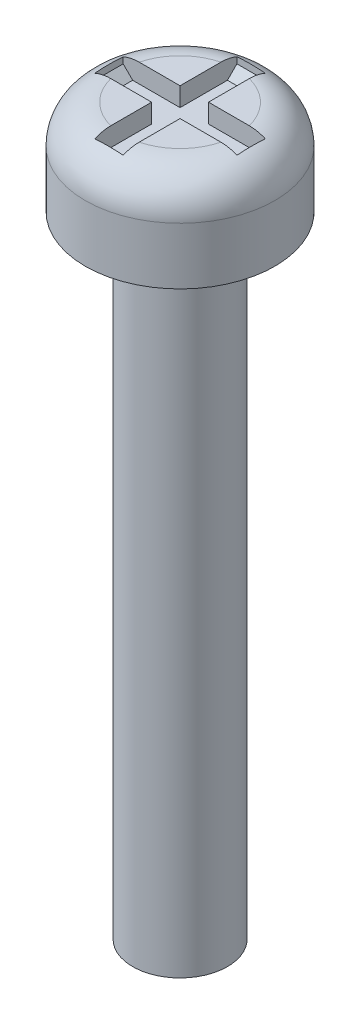
SolidWorks part; units mm, degrees
ref_plane "Front Plane" through (0, 0, 0) normal (0, 0, 1) x (1, 0, 0)
ref_plane "Top Plane" through (0, 0, 0) normal (0, 1, 0) x (1, 0, 0)
ref_plane "Right Plane" through (0, 0, 0) normal (1, 0, 0) x (0, 0, -1)
sketch "Sketch1" plane through (0, 0, 0) normal (0, 1, 0) x (1, 0, 0)
  circle A0 centre (0, 0) radius 2
  dimension "D1" = 4
extrude "Boss-Extrude1" add sketch "Sketch1" along normal blind 2
fillet "Fillet1" radius 0.8 1 edges at (0, 2, 2)
sketch "Sketch2" plane through (0, 2, 0) normal (0, 1, 0) x (1, 0, 0)
  line L1 (-1.5, 0.3) -> (1.5, 0.3)
  line L2 (-1.5, 0.3) -> (-1.5, -0.3)
  line L3 (-1.5, -0.3) -> (1.5, -0.3)
  line L4 (1.5, 0.3) -> (1.5, -0.3)
  line L5 (-1.5, 0.3) -> (1.5, -0.3) construction
  line L6 (-1.5, -0.3) -> (1.5, 0.3) construction
  line L7 (-0.3, -1.5) -> (0.3, -1.5)
  line L8 (-0.3, -1.5) -> (-0.3, 1.5)
  line L9 (-0.3, 1.5) -> (0.3, 1.5)
  line L10 (0.3, -1.5) -> (0.3, 1.5)
  line L11 (-0.3, -1.5) -> (0.3, 1.5) construction
  line L12 (-0.3, 1.5) -> (0.3, -1.5) construction
  point P0 (0, 0)
  point P6 (0, 0)
  circle M9 centre (0, 0) radius 1.2
  dimension "D1" = 1.5
  dimension "D2" = 0.6
extrude "Cut-Extrude1" cut sketch "Sketch2" against normal blind 0.4 contours L3 L8 L1 M9 | L1 L10 L8 M9 | L2 L3 L1 M9 | L10 L9 L8 M9 | L10 L3 L1 M9 | L4 L1 L3 M9 | L3 L10 L1 L8 | L10 L3 L8 M9 | L7 L10 L8 M9
chamfer "Chamfer1" distance 0.2 angle 45 4 edges at (0, 1.6, 1.5) (1.5, 1.6, 0) (-1.5, 1.6, 0) (0, 1.6, -1.5)
sketch "Sketch3" plane through (0, 0, 0) normal (0, -1, 0) x (1, 0, 0)
  circle A0 centre (0, 0) radius 1
  dimension "D1" = 2
extrude "Boss-Extrude2" add sketch "Sketch3" along normal blind 13.3
